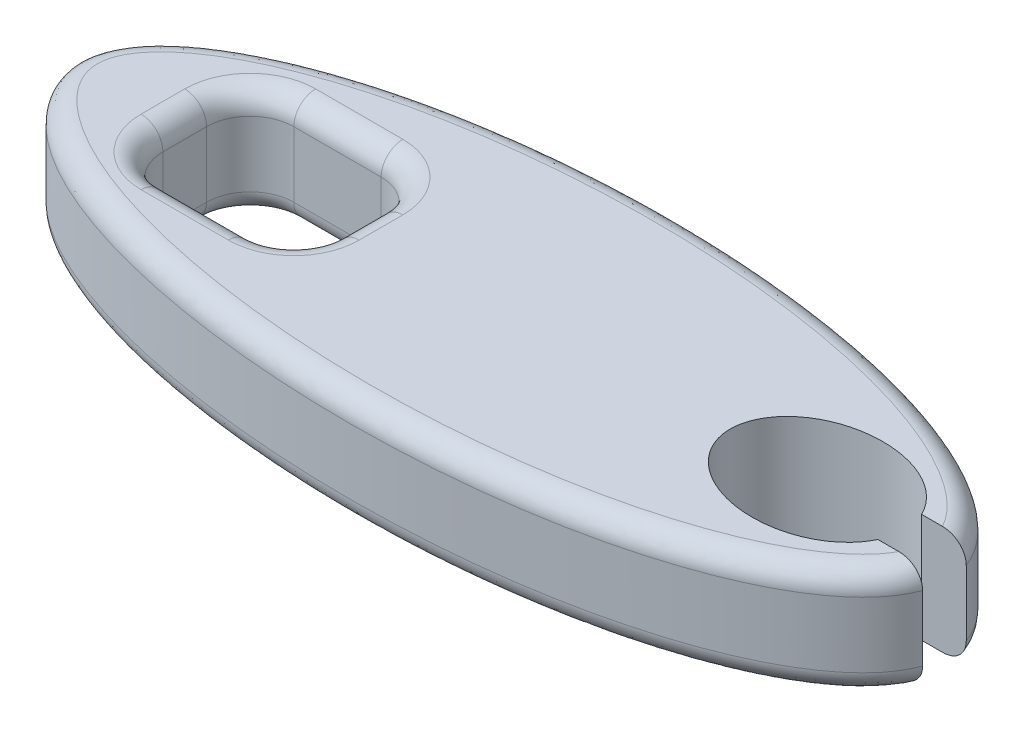
SolidWorks part; units mm, degrees
ref_plane "前视基准面" through (0, 0, 0) normal (0, 0, 1) x (1, 0, 0)
ref_plane "上视基准面" through (0, 0, 0) normal (0, 1, 0) x (1, 0, 0)
ref_plane "右视基准面" through (0, 0, 0) normal (1, 0, 0) x (0, 0, -1)
other "Configuration Table"
sketch "草图1" plane through (0, 0, 0) normal (0, 1, 0) x (1, 0, 0)
  line L0 (4, 10.9465) -> (4, -8.3515) construction
  line L1 (6, 10.6163) -> (6, -9.4492) construction
  line L2 (6, 0) -> (-4, 0) construction
  line L3 (-21, 3) -> (-29, 3)
  line L4 (-21, 3) -> (-21, -3)
  line L5 (-21, -3) -> (-29, -3)
  line L6 (-29, 3) -> (-29, -3)
  line L7 (3.7712, 1) -> (6, 1)
  line L8 (3.7712, 1) -> (3.7712, -1)
  line L9 (3.7712, -1) -> (6, -1)
  line L10 (6, 1) -> (6, -1)
  ellipse E0 centre (0, 0) end of major axis (4, 0) minor radius 3
  ellipse E1 centre (-14, 0) end of major axis (-34, 0) minor radius 7.5
  dimension "D1" = 8
  dimension "D2" = 6
  dimension "D3" = 40
  dimension "D4" = 15
  dimension "D5" = 2
  dimension "D6" = 8
  dimension "D7" = 21
  dimension "D8" = 2
extrude "凸台-拉伸1" add sketch "草图1" along normal blind 5 contours E1 L7 E0 L9 | L3 L6 L5 L4
fillet "圆角1" radius 2 4 edges at (-29, 2.5, 3) (-21, 2.5, 3) (-21, 2.5, -3) (-29, 2.5, -3)
fillet "圆角2" radius 1 18 edges at (-29, 0, 0) (-28.4142, 0, -2.4142) (-25, 0, -3) (-21.5858, 0, -2.4142) (-21, 0, 0) (-21.5858, 0, 2.4142) (-25, 0, 3) (-21.5858, 5, -2.4142) (-21, 5, 0) (-21.5858, 5, 2.4142) (-25, 5, 3) (-28.4142, 5, 2.4142) (-29, 5, 0) (-28.4142, 5, -2.4142) (-28.4142, 0, 2.4142) (-25, 5, -3) (-34, 0, 0) (-34, 5, 0)
